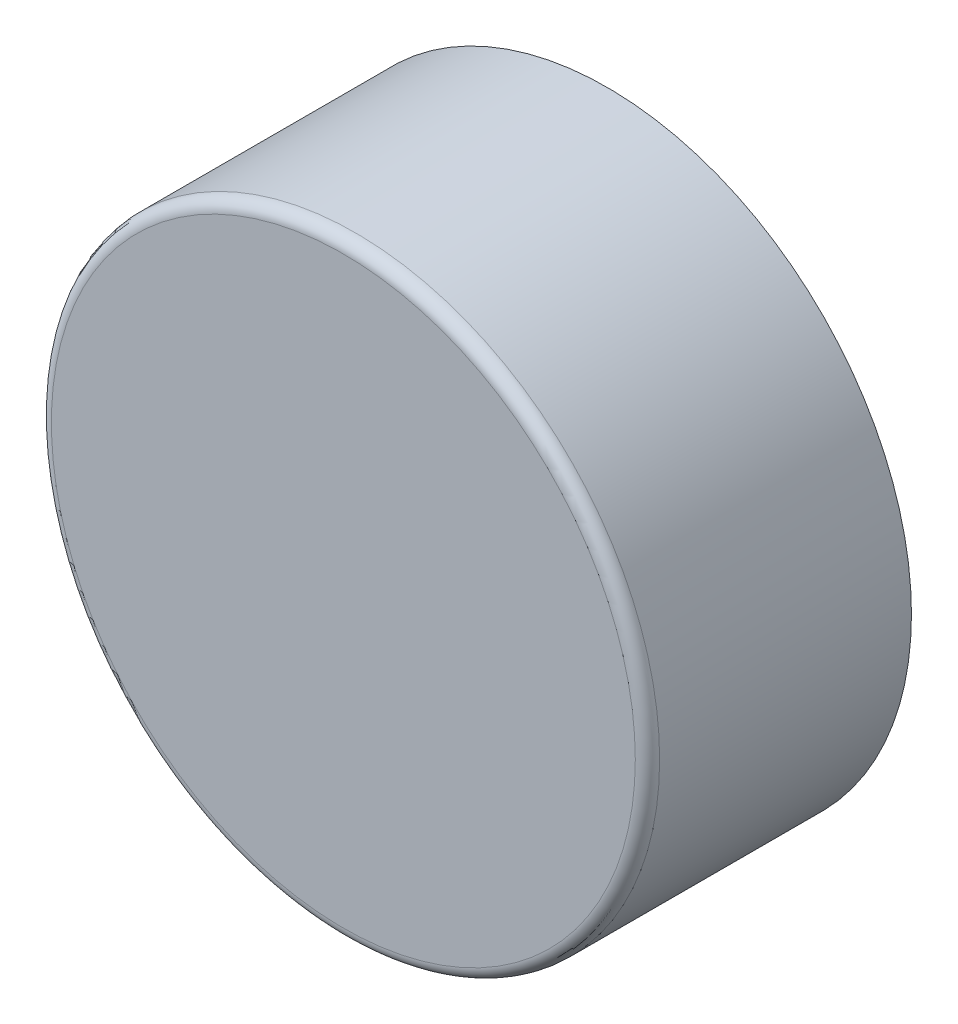
SolidWorks part; units mm, degrees
ref_plane "Plan de face" through (0, 0, 0) normal (0, 0, 1) x (1, 0, 0)
ref_plane "Plan de dessus" through (0, 0, 0) normal (0, 1, 0) x (1, 0, 0)
ref_plane "Plan de droite" through (0, 0, 0) normal (1, 0, 0) x (0, 0, -1)
sketch "Esquisse1" plane through (0, 0, 0) normal (0, 0, 1) x (1, 0, 0)
  circle A0 centre (0, 0) radius 2.5
  point P3 (14.6691, 3.8969)
  dimension "D1" = 5
extrude "Boss.-Extru.1" add sketch "Esquisse1" along normal up to surface (2.17 mm away) contours A0
fillet "Congé1" radius 0.1 1 edges at (2.5, 0, 2.17)
